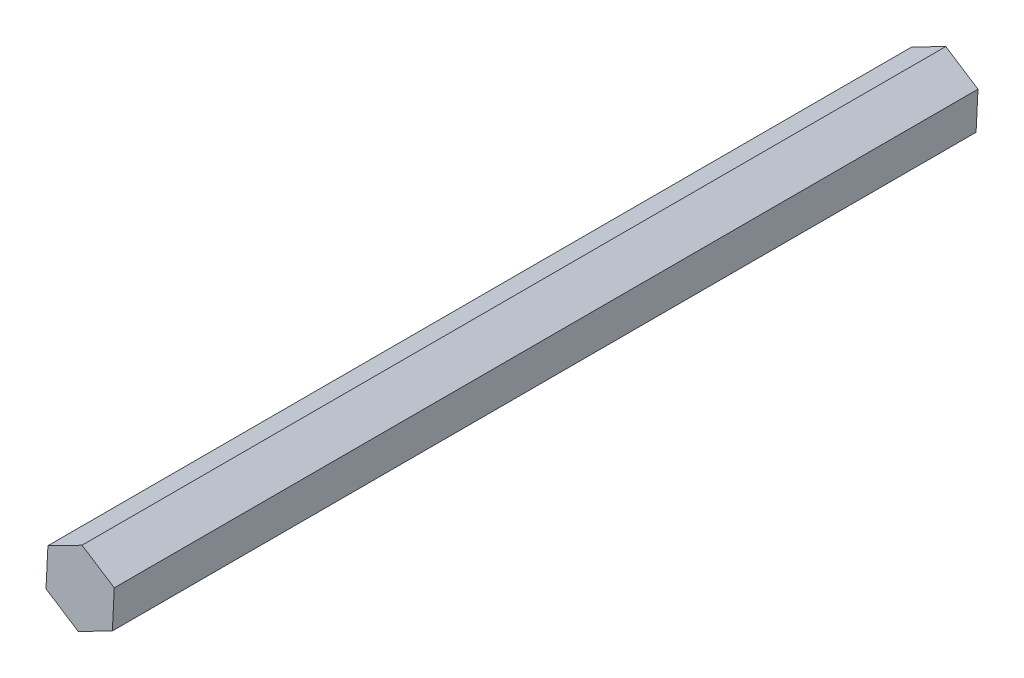
SolidWorks part; units mm, degrees
ref_plane "Front Plane" through (0, 0, 0) normal (0, 0, 1) x (1, 0, 0)
ref_plane "Top Plane" through (0, 0, 0) normal (0, 1, 0) x (1, 0, 0)
ref_plane "Right Plane" through (0, 0, 0) normal (1, 0, 0) x (0, 0, -1)
sketch "Sketch1" plane through (0, 0, 0) normal (0, 0, 1) x (1, 0, 0)
  line L1 (-6.1589, 3.9788) -> (-6.5252, -3.3444)
  line L2 (-6.5252, -3.3444) -> (-0.3663, -7.3232)
  line L3 (-0.3663, -7.3232) -> (6.1589, -3.9788)
  line L4 (6.1589, -3.9788) -> (6.5252, 3.3444)
  line L5 (6.5252, 3.3444) -> (0.3663, 7.3232)
  line L6 (0.3663, 7.3232) -> (-6.1589, 3.9788)
  circle A0 centre (0, 0) radius 6.35 construction
  dimension "D1" = 12.7
extrude "Boss-Extrude1" add sketch "Sketch1" along normal blind 165.1
